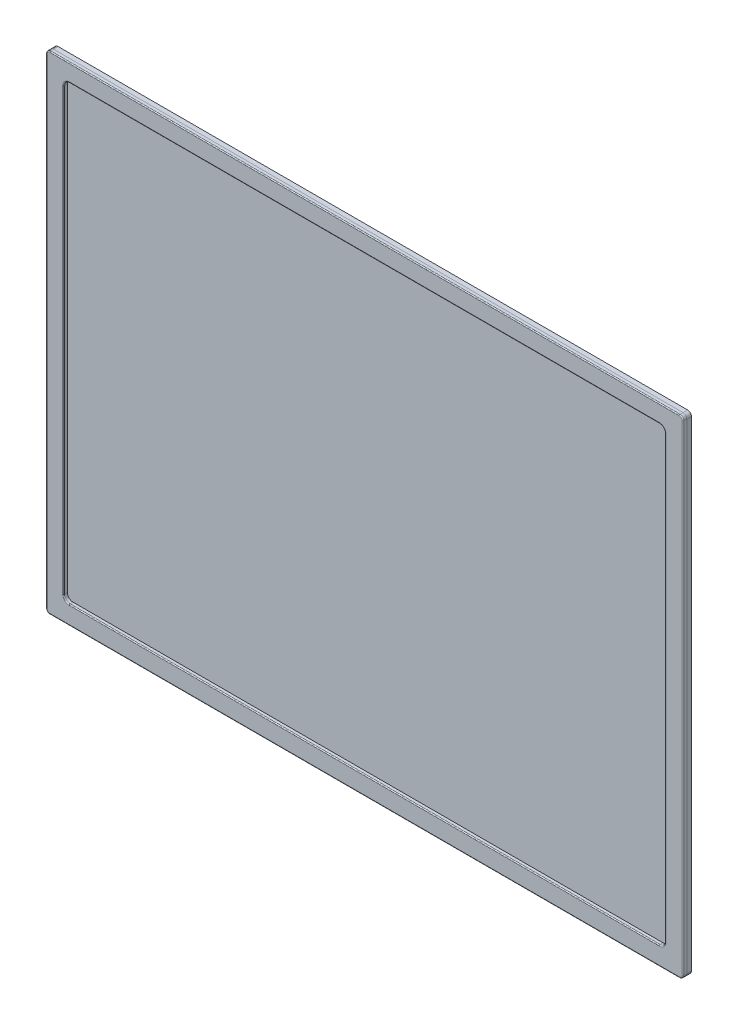
SolidWorks part; units mm, degrees
ref_plane "Front Plane" through (0, 0, 0) normal (0, 0, 1) x (1, 0, 0)
ref_plane "Top Plane" through (0, 0, 0) normal (0, 1, 0) x (1, 0, 0)
ref_plane "Right Plane" through (0, 0, 0) normal (1, 0, 0) x (0, 0, -1)
sketch "Model" plane through (0, 0, 0) normal (0, 0, 1) x (1, 0, 0)
  line L0 (41630.6, -357.0108) -> (7137.4, -357.0108)
  line L1 (6934.2, -560.2108) -> (6934.2, -26873.2)
  line L2 (7137.4, -27076.4) -> (41630.6, -27076.4)
  line L3 (41833.8, -26873.2) -> (41833.8, -560.2108)
  line L4 (40538.4, -26060.4) -> (8204.2, -26060.4)
  line L5 (7899.4, -25755.6) -> (7899.4, -1627.0108)
  line L6 (8204.2, -1322.2108) -> (40538.4, -1322.2108)
  line L7 (40843.2, -1627.0108) -> (40843.2, -25755.6)
  spline S0 degree 3 poles (7137.4, -357.0108) (7025.6394, -357.0108) (6934.2, -448.4501) (6934.2, -560.2108) knots 1 1 1 1 2 2 2 2
  spline S1 degree 3 poles (6934.2, -26873.2) (6934.2, -26984.9575) (7025.6394, -27076.4) (7137.4, -27076.4) knots 3 3 3 3 4 4 4 4
  spline S2 degree 3 poles (41630.6, -27076.4) (41742.3606, -27076.4) (41833.8, -26984.9575) (41833.8, -26873.2) knots 5 5 5 5 6 6 6 6
  spline S3 degree 3 poles (41833.8, -560.2108) (41833.8, -448.4501) (41742.3606, -357.0108) (41630.6, -357.0108) knots 7 7 7 7 8 8 8 8
  spline S4 degree 3 poles (40843.2, -25755.6) (40843.2, -25923.2394) (40706.0394, -26060.4) (40538.4, -26060.4) knots 0 0 0 0 1 1 1 1
  spline S5 degree 3 poles (8204.2, -26060.4) (8036.5606, -26060.4) (7899.4, -25923.2394) (7899.4, -25755.6) knots 2 2 2 2 3 3 3 3
  spline S6 degree 3 poles (7899.4, -1627.0108) (7899.4, -1459.3714) (8036.5606, -1322.2108) (8204.2, -1322.2108) knots 4 4 4 4 5 5 5 5
  spline S7 degree 3 poles (40538.4, -1322.2108) (40706.0394, -1322.2108) (40843.2, -1459.3714) (40843.2, -1627.0108) knots 6 6 6 6 7 7 7 7
extrude "Boss-Extrude1" add sketch "Model" along normal blind 203.2
fillet "Fillet1" radius 50.8 16 edges at (6934.2, -13716.7054, 203.2) (24384, -357.0108, 203.2) (41833.8, -13716.7054, 203.2) (24371.3, -1322.2108, 203.2) (40843.2, -13691.3054, 203.2) (24371.3, -26060.4, 203.2) (24384, -27076.4, 203.2) (7899.4, -13691.3054, 203.2)
sketch "Sketch4" plane through (0, 0, 0) normal (0, 0, 1) x (1, 0, 0)
  line L0 (41630.6, -357.0108) -> (7137.4, -357.0108)
  line L1 (6934.2, -560.2108) -> (6934.2, -26873.2)
  line L2 (7137.4, -27076.4) -> (41630.6, -27076.4)
  line L3 (41833.8, -26873.2) -> (41833.8, -560.2108)
  spline S0 degree 3 poles (7137.4, -357.0108) (7025.6394, -357.0108) (6934.2, -448.4501) (6934.2, -560.2108) knots 1 1 1 1 2 2 2 2
  spline S1 degree 3 poles (6934.2, -26873.2) (6934.2, -26984.9575) (7025.6394, -27076.4) (7137.4, -27076.4) knots 3 3 3 3 4 4 4 4
  spline S2 degree 3 poles (41630.6, -27076.4) (41742.3606, -27076.4) (41833.8, -26984.9575) (41833.8, -26873.2) knots 5 5 5 5 6 6 6 6
  spline S3 degree 3 poles (41833.8, -560.2108) (41833.8, -448.4501) (41742.3606, -357.0108) (41630.6, -357.0108) knots 7 7 7 7 8 8 8 8
extrude "Boss-Extrude2" add sketch "Sketch4" against normal blind 254 separate body contours L0 S0 L1 S1 L2 S2 L3 S3
